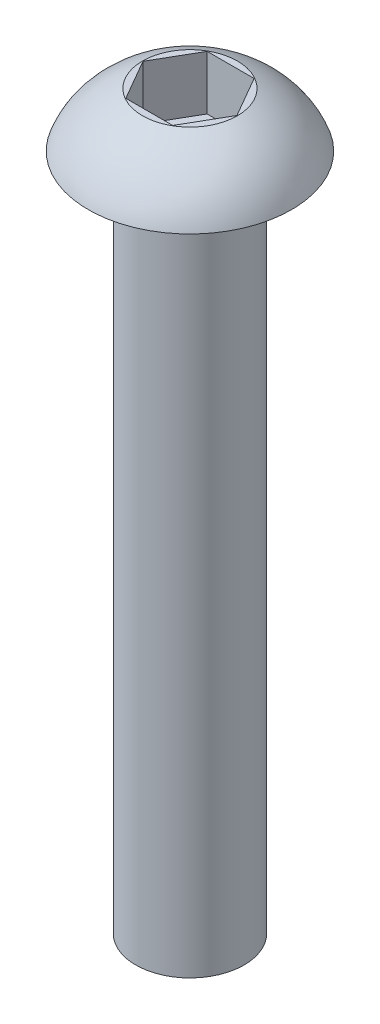
SolidWorks part; units mm, degrees
ref_plane "前视基准面" through (0, 0, 0) normal (0, 0, 1) x (1, 0, 0)
ref_plane "上视基准面" through (0, 0, 0) normal (0, 1, 0) x (1, 0, 0)
ref_plane "右视基准面" through (0, 0, 0) normal (1, 0, 0) x (0, 0, -1)
other "Configuration Table"
sketch "Sketch15" plane through (0, 0, 0) normal (1, 0, 0) x (0, 0, -1)
  line L0 (-1, -12.5) -> (-1, 12.5)
  line L1 (-1, 12.5) -> (1, 12.5)
  line L2 (-1, 12.5) -> (-1, -12.5)
  line L3 (-1, -12.5) -> (1, -12.5)
  line L4 (1, 12.5) -> (1, -12.5)
  line L5 (-1, 12.5) -> (1, -12.5) construction
  line L6 (-1, -12.5) -> (1, 12.5) construction
  line L7 (1, 12.5) -> (2.75, 12.5)
  line L8 (-1, 12.5) -> (0.75, 12.5)
  line L9 (0.75, 12.5) -> (0.75, 14.5)
  spline S0 degree 2 poles (0.75, 14.5) (2.291, 13.8196) (2.75, 12.5) knots 0 0 0 0.856056 0.856056 0.856056
  point P0 (0, 0)
  dimension "D1" = 25
  dimension "D2" = 2
  dimension "D3" = 3.75
  dimension "D4" = 1.75
  dimension "D5" = 2
revolve "Revolve3" add sketch "Sketch15" angle 360 about L0
ref_plane "Plane4" through (0, 12.5, 0) normal (0, 1, 0) x (1, 0, 0)
sketch "Sketch19" plane through (0, 12.5, 0) normal (0, 1, 0) x (1, 0, 0)
  line L1 (1.7321, -1) -> (0.866, 0.5)
  line L2 (0.866, 0.5) -> (-0.866, 0.5)
  line L3 (-0.866, 0.5) -> (-1.7321, -1)
  line L4 (-1.7321, -1) -> (-0.866, -2.5)
  line L5 (-0.866, -2.5) -> (0.866, -2.5)
  line L6 (0.866, -2.5) -> (1.7321, -1)
  circle A0 centre (0, -1) radius 1.5 construction
  circle A1 centre (0, -1) radius 1.75
  point P9 (0.0901, -1.0712)
  point P10 (0, -1.0111)
  point P11 (-0.3472, -1.6125)
  point P12 (0, -1)
  point P14 (0, -1)
  point P15 (0, -1)
  point P16 (0, -1)
  dimension "D1" = 3
extrude "Boss-Extrude11" add sketch "Sketch19" along normal blind 2
